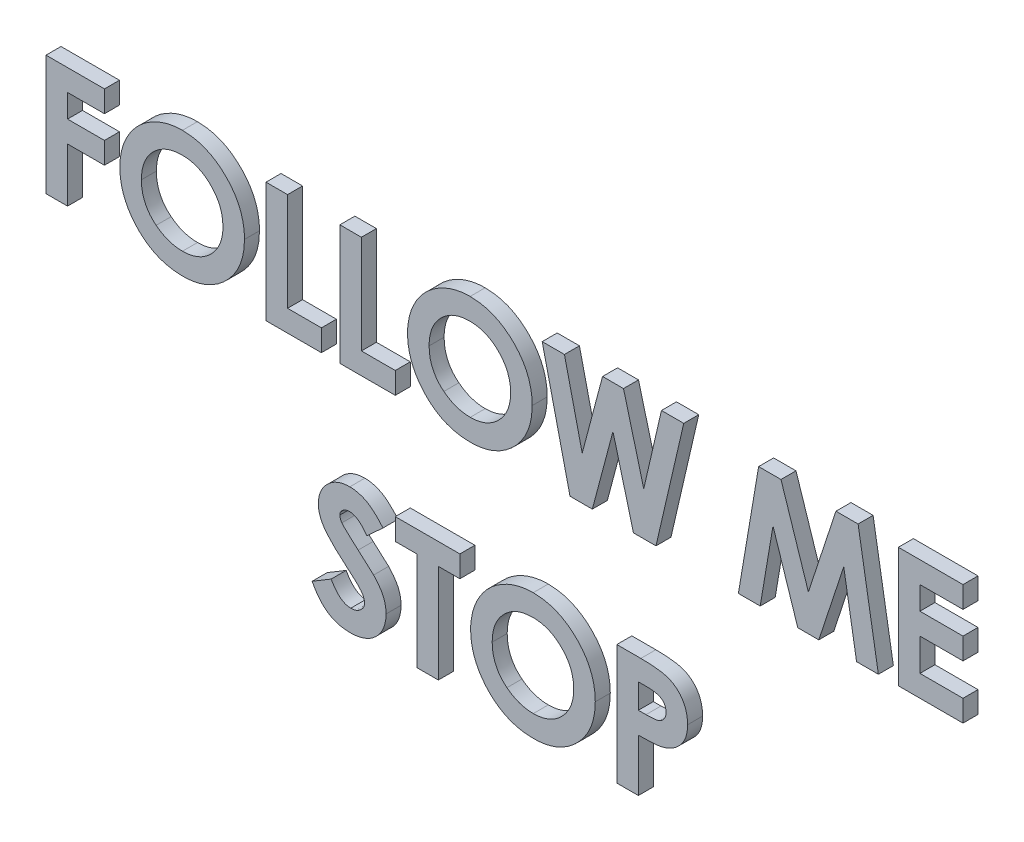
SolidWorks part; units mm, degrees
material "ABS"
ref_plane "Front Plane" through (0, 0, 0) normal (0, 0, 1) x (1, 0, 0)
ref_plane "Top Plane" through (0, 0, 0) normal (0, 1, 0) x (1, 0, 0)
ref_plane "Right Plane" through (0, 0, 0) normal (1, 0, 0) x (0, 0, -1)
sketch "Sketch1" plane through (0, 0, 0) normal (0, 0, 1) x (1, 0, 0)
  line L0 (0, 21) -> (75, 21) construction
  line L1 (0, 0) -> (75, 0) construction
  line L2 (0, 0) -> (0, 35) construction
  line L3 (0, 35) -> (75, 35) construction
  line L4 (75, 0) -> (75, 35) construction
  line L5 (0, 6) -> (75, 6) construction
  text T0 "FOLLOW ME" font "Century Gothic" height 8
  text T1 "STOP" font "Century Gothic" height 8
  dimension "D1" = 6
  dimension "D2" = 14
  dimension "D3" = 35
  dimension "D4" = 75
extrude "Boss-Extrude1" add sketch "Sketch1" along normal blind 1
